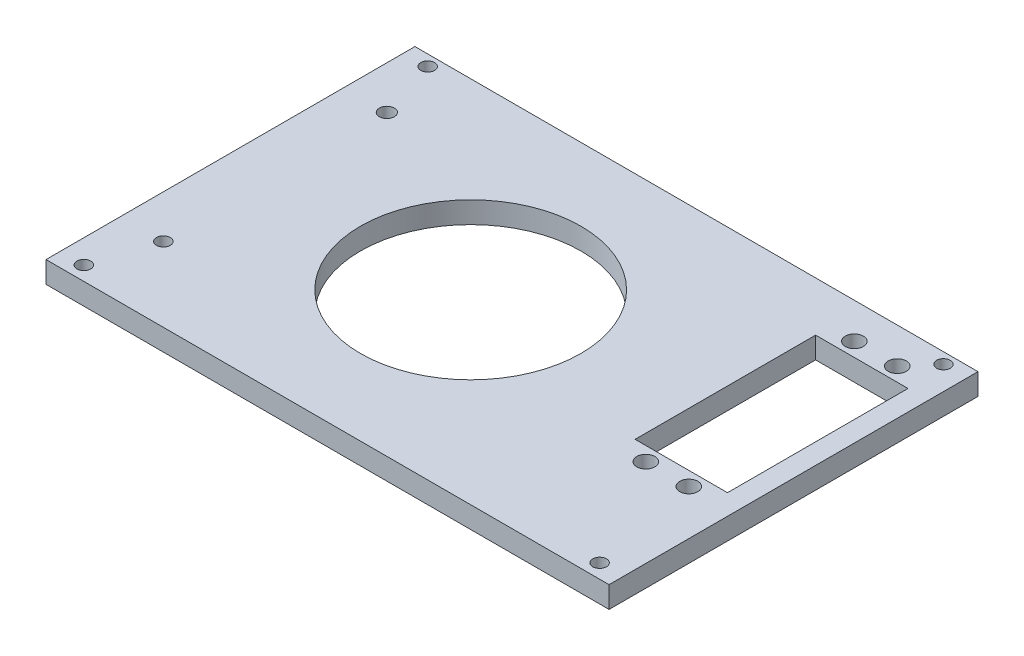
SolidWorks part; units mm, degrees
ref_plane "Front" through (0, 0, 0) normal (0, 0, 1) x (1, 0, 0)
ref_plane "Top" through (0, 0, 0) normal (0, 1, 0) x (1, 0, 0)
ref_plane "Right" through (0, 0, 0) normal (1, 0, 0) x (0, 0, -1)
sketch "Sketch1" plane through (0, 0, 0) normal (0, 1, 0) x (1, 0, 0)
  line L0 (65.5, 42.532) -> (65.5, -43.3038)
  line L1 (65.5, -43.3038) -> (-65.5, -43.3038)
  line L2 (-65.5, 42.532) -> (-65.5, -43.3038)
  line L3 (-65.5, 42.532) -> (65.5, 42.532)
  line L5 (39.25, 31) -> (60.75, 31)
  line L6 (39.25, 31) -> (39.25, -11)
  line L13 (39.25, -11) -> (60.75, -11)
  line L14 (60.75, 31) -> (60.75, -11)
  line L15 (39.25, 31) -> (60.75, -11) construction
  line L16 (39.25, -11) -> (60.75, 31) construction
  circle A0 centre (-55.5, -26) radius 1.6
  circle A1 centre (-60, -40) radius 1.6
  circle A2 centre (60, -40) radius 1.6
  circle A3 centre (60, 40) radius 1.6
  circle A4 centre (45, 34.25) radius 2.1
  circle A5 centre (55, 34.25) radius 2.1
  circle A6 centre (-55.5, 26) radius 1.75
  circle A7 centre (45, -14.25) radius 2.1
  circle A8 centre (-10, 0) radius 25.65
  circle A9 centre (-60, 40) radius 1.6
  circle A10 centre (55, -14.25) radius 2.1
  point P0 (0, 0)
  point P5 (50, 10)
  point P8 (50, 10)
  dimension "D3" = 3.2
  dimension "D13" = 4.2
  dimension "D19" = 51.3
  dimension "D20" = 131
  dimension "D18" = 40
  dimension "D12" = 3.5
  dimension "D15" = 60
  dimension "D7" = 26
  dimension "D2" = 50
  dimension "D4" = 10
  dimension "D5" = 10
  dimension "D8" = 5
  dimension "D9" = 24.25
  dimension "D11" = 55.5
  dimension "D14" = 26
  dimension "D17" = 40
  dimension "D21" = 2
  dimension "D22" = 5.5
  dimension "D16" = 60
  dimension "D6" = 55.5
  dimension "D25" = 21.5
  dimension "D26" = 42
extrude "Boss-Extrude1" add sketch "Sketch1" along normal blind 5
